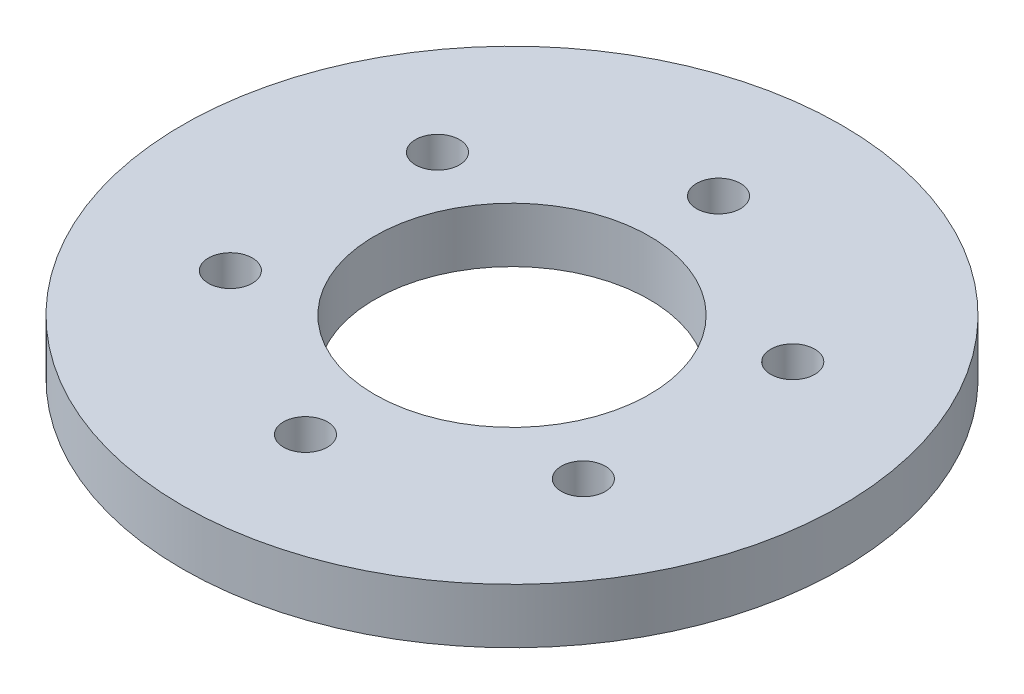
SolidWorks part; units mm, degrees
ref_plane "Front Plane" through (0, 0, 0) normal (0, 0, 1) x (1, 0, 0)
ref_plane "Top Plane" through (0, 0, 0) normal (0, 1, 0) x (1, 0, 0)
ref_plane "Right Plane" through (0, 0, 0) normal (1, 0, 0) x (0, 0, -1)
sketch "Sketch1" plane through (0, 0, 0) normal (0, 1, 0) x (1, 0, 0)
  line L0 (15.875, -6.35) -> (-15.875, -6.35) construction
  line L5 (-38.1, 44.45) -> (38.1, -44.45) construction
  line L6 (-38.1, -44.45) -> (38.1, 44.45) construction
  circle A1 centre (0, -6.35) radius 15.875
  circle A6 centre (0, -6.35) radius 23.876 construction
  circle A7 centre (-20.632, 5.6659) radius 2.54
  circle A8 centre (-20.7512, -18.159) radius 2.54
  circle A9 centre (20.8822, 5.2257) radius 2.54
  circle A10 centre (20.4961, -18.5964) radius 2.54
  circle A11 centre (0, 17.526) radius 2.54
  circle A12 centre (0, -30.226) radius 2.54
  circle A13 centre (0, -6.35) radius 38.1
  point P0 (0, 0)
  dimension "D3" = 31.75
  dimension "D6" = 47.752
  dimension "D7" = 5.08
  dimension "D8" = 5.08
  dimension "D9" = 5.08
  dimension "D10" = 5.08
  dimension "D16" = 5.08
  dimension "D1" = 88.9
  dimension "D2" = 76.2
  dimension "D12" = 23.8252
  dimension "D13" = 41.2496
  dimension "D14" = 23.8252
extrude "Boss-Extrude1" add sketch "Sketch1" along normal blind 6.35
